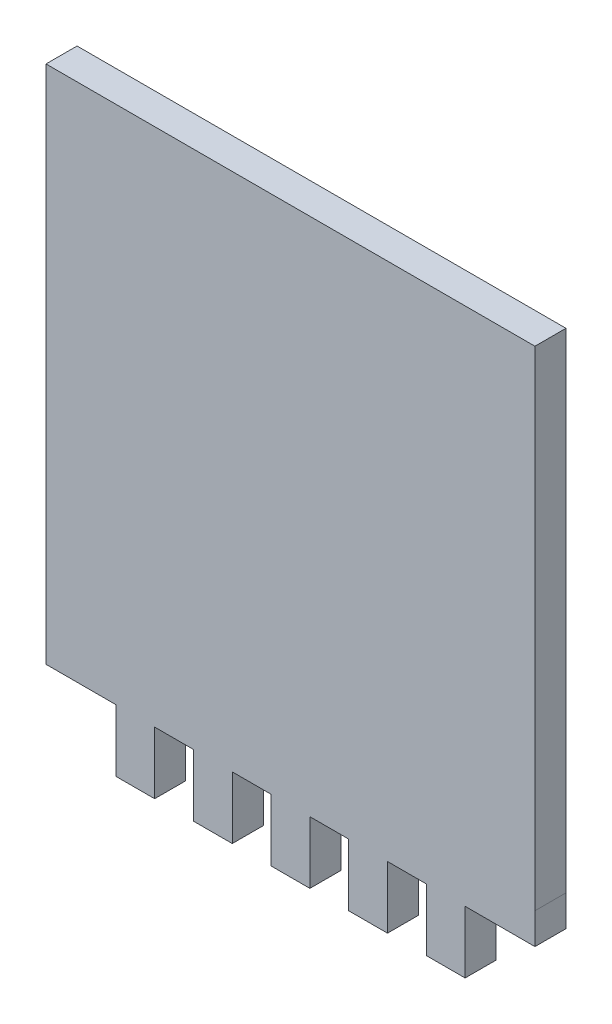
SolidWorks part; units mm, degrees
ref_plane "Front Plane" through (0, 0, 0) normal (0, 0, 1) x (1, 0, 0)
ref_plane "Top Plane" through (0, 0, 0) normal (0, 1, 0) x (1, 0, 0)
ref_plane "Right Plane" through (0, 0, 0) normal (1, 0, 0) x (0, 0, -1)
sketch "Sketch1" plane through (0, 0, 0) normal (0, 0, 1) x (1, 0, 0)
  line L0 (-32.321, -5.0053) -> (-32.321, 34.9947)
  line L1 (-32.321, 34.9947) -> (5.779, 34.9947)
  line L2 (5.779, 34.9947) -> (5.779, -5.0053)
  line L3 (5.779, -5.0053) -> (26.729, -5.0053)
  line L4 (26.729, -5.0053) -> (26.729, -10.0853)
  line L5 (26.729, -10.0853) -> (-53.271, -10.0853)
  line L6 (-53.271, -10.0853) -> (-53.271, -5.0053)
  line L7 (-53.271, -5.0053) -> (-32.321, -5.0053)
  dimension "D1" = 38.1
  dimension "D2" = 80
  dimension "D3" = 20.9499
  dimension "D4" = 5.08
  dimension "D5" = 40
  dimension "D6" = 5.08
extrude "Boss-Extrude1" add sketch "Sketch1" along normal blind 5.08
sketch "Sketch2" plane through (0, 0, 5.08) normal (0, 0, 1) x (1, 0, 0)
  line L0 (-13.271, 34.9947) -> (-13.271, -21.5688) construction
  line L1 (5.779, 34.9947) -> (-32.321, 34.9947) construction
  line L2 (-10.096, -10.0853) -> (-10.096, -20.2453)
  line L3 (-53.271, -10.0853) -> (26.729, -10.0853) construction
  line L4 (-10.096, -20.2453) -> (-16.446, -20.2453)
  line L5 (-41.846, -10.0853) -> (-41.846, -20.2453)
  line L6 (-3.746, -10.0853) -> (2.604, -10.0853)
  line L7 (-3.746, -10.0853) -> (-3.746, -20.2453)
  line L8 (-3.746, -20.2453) -> (2.604, -20.2453)
  line L9 (2.604, -10.0853) -> (2.604, -20.2453)
  line L10 (8.954, -10.0853) -> (15.304, -10.0853)
  line L11 (8.954, -10.0853) -> (8.954, -20.2453)
  line L12 (8.954, -20.2453) -> (15.304, -20.2453)
  line L13 (15.304, -10.0853) -> (15.304, -20.2453)
  line L14 (-35.496, -20.2453) -> (-41.846, -20.2453)
  line L15 (-35.496, -10.0853) -> (-35.496, -20.2453)
  line L16 (-35.496, -10.0853) -> (-41.846, -10.0853)
  line L17 (-29.146, -10.0853) -> (-29.146, -20.2453)
  line L18 (-22.796, -20.2453) -> (-29.146, -20.2453)
  line L19 (-22.796, -10.0853) -> (-22.796, -20.2453)
  line L20 (-22.796, -10.0853) -> (-29.146, -10.0853)
  line L21 (-16.446, -10.0853) -> (-16.446, -20.2453)
  point P26 (-13.271, -20.2453)
  line M12 (-53.271, -10.0853) -> (26.729, -10.0853)
  dimension "D1" = 10.16
  dimension "D2" = 10.16
  dimension "D3" = 10.16
  dimension "D4" = 3.175
  dimension "D5" = 6.35
  dimension "D6" = 6.35
  dimension "D7" = 6.35
  dimension "D8" = 6.35
extrude "Boss-Extrude2" add sketch "Sketch2" against normal blind 5.08 contours L15 L5 L14 M12 | L19 L17 L18 M12 | L0 L21 L4 M12 | L0 L4 L2 M12 | L9 L7 L8 M12 | L13 L11 L12 M12
sketch "Sketch3" plane through (0, 0, 5.08) normal (0, 0, 1) x (1, 0, 0)
  line L0 (5.779, 34.9947) -> (-32.321, 34.9947) construction
  line L1 (-53.271, 74.9947) -> (26.729, 74.9947)
  line L2 (-53.271, 74.9947) -> (-53.271, -5.0053)
  line L3 (-53.271, -5.0053) -> (26.729, -5.0053)
  line L4 (26.729, 74.9947) -> (26.729, -5.0053)
  line L5 (-53.271, 74.9947) -> (26.729, -5.0053) construction
  line L6 (-53.271, -5.0053) -> (26.729, 74.9947) construction
  point P0 (-13.271, 34.9947)
  dimension "D1" = 80
  dimension "D2" = 80
extrude "Boss-Extrude3" add sketch "Sketch3" against normal blind 5.08
